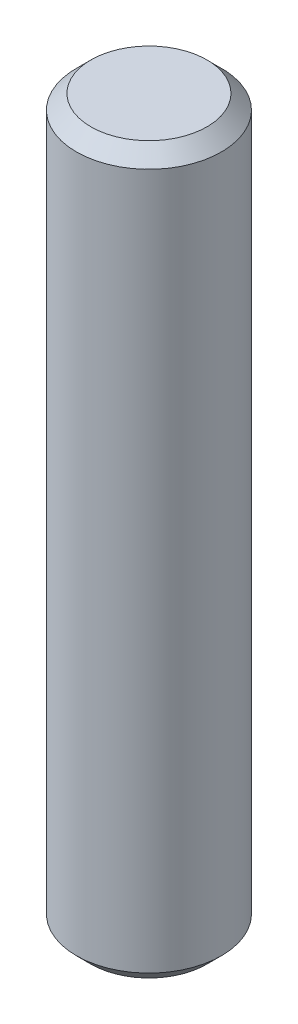
SolidWorks part; units mm, degrees
ref_plane "Front Plane" through (0, 0, 0) normal (0, 0, 1) x (1, 0, 0)
ref_plane "Top Plane" through (0, 0, 0) normal (0, 1, 0) x (1, 0, 0)
ref_plane "Right Plane" through (0, 0, 0) normal (1, 0, 0) x (0, 0, -1)
sketch "Sketch1" plane through (0, 0, 0) normal (0, 1, 0) x (1, 0, 0)
  circle A0 centre (0, 0) radius 5
  dimension "D1" = 10
extrude "Boss-Extrude1" add sketch "Sketch1" along normal blind 50
chamfer "Chamfer1" distance 1 angle 45 2 edges at (0, 50, 5) (0, 0, 5)
